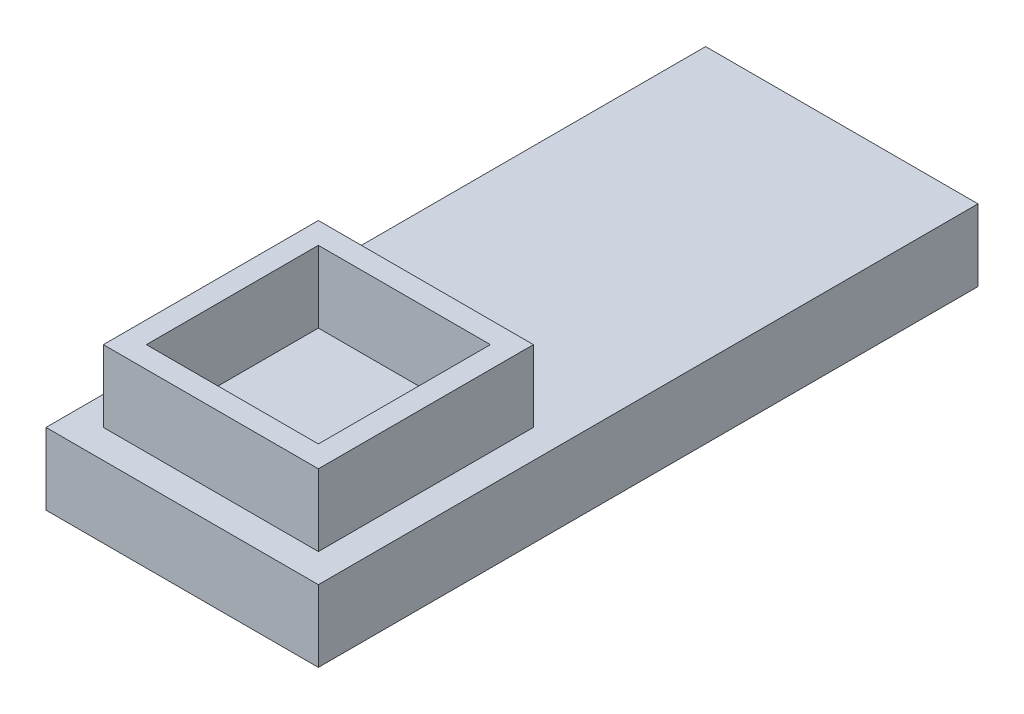
SolidWorks part; units mm, degrees
ref_plane "Front Plane" through (0, 0, 0) normal (0, 0, 1) x (1, 0, 0)
ref_plane "Top Plane" through (0, 0, 0) normal (0, 1, 0) x (1, 0, 0)
ref_plane "Right Plane" through (0, 0, 0) normal (1, 0, 0) x (0, 0, -1)
sketch "Sketch5" plane through (0, 0, 0) normal (0, 1, 0) x (1, 0, 0)
  line L1 (-11.5829, 21.1277) -> (18.4171, 21.1277)
  line L2 (-11.5829, 21.1277) -> (-11.5829, -8.8723)
  line L3 (-11.5829, -8.8723) -> (18.4171, -8.8723)
  line L4 (18.4171, 21.1277) -> (18.4171, -8.8723)
  line L5 (-8.5829, 18.1277) -> (15.4171, 18.1277)
  line L6 (-8.5829, 18.1277) -> (-8.5829, -5.8723)
  line L7 (-8.5829, -5.8723) -> (15.4171, -5.8723)
  line L8 (15.4171, 18.1277) -> (15.4171, -5.8723)
  dimension "D1" = 3
  dimension "D2" = 3
  dimension "D3" = 3
  dimension "D4" = 3
  dimension "D5" = 30
  dimension "D6" = 30
extrude "Boss-Extrude4" add sketch "Sketch5" along normal blind 10
sketch "Sketch6" plane through (0, 0, 0) normal (0, 1, 0) x (1, 0, 0)
  line L0 (-11.5829, 21.1277) -> (-11.5829, -8.8723) construction
  line L1 (-15.5829, -12.8723) -> (22.4171, -12.8723)
  line L2 (-15.5829, -12.8723) -> (-15.5829, 79.1533)
  line L3 (-15.5829, 79.1533) -> (22.4171, 79.1533)
  line L4 (22.4171, -12.8723) -> (22.4171, 79.1533)
  line L5 (18.4171, -8.8723) -> (18.4171, 21.1277) construction
  line L6 (-11.5829, -8.8723) -> (18.4171, -8.8723) construction
  dimension "D1" = 4
  dimension "D2" = 4
  dimension "D3" = 4
extrude "Boss-Extrude5" add sketch "Sketch6" against normal blind 10
